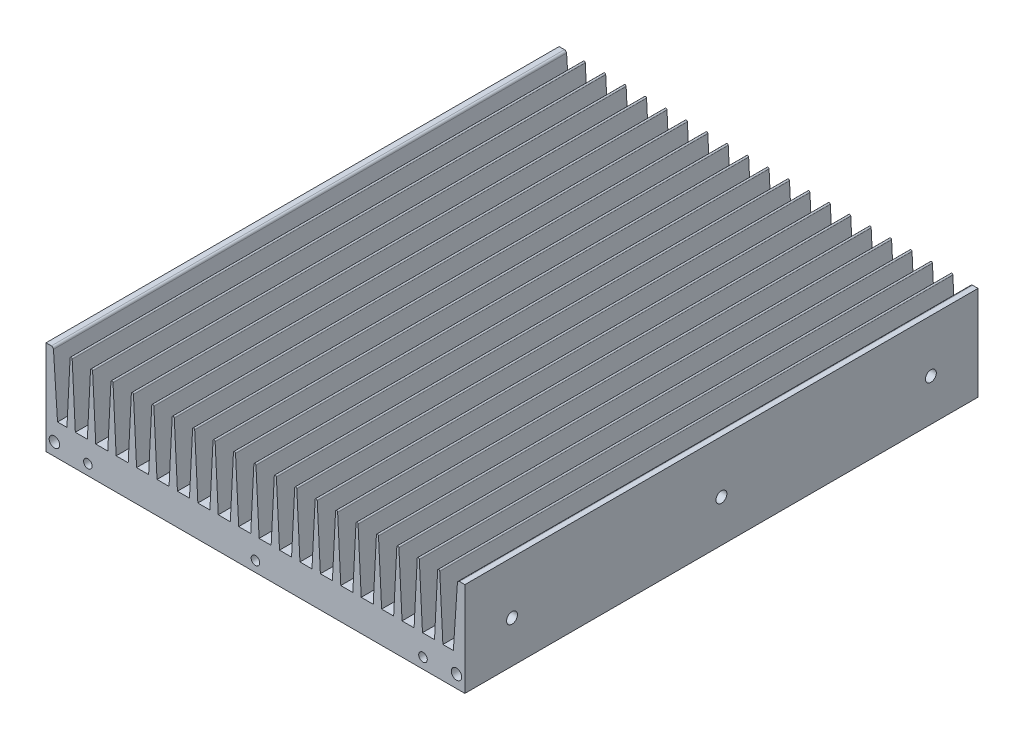
SolidWorks part; units mm, degrees
ref_plane "Спереди" through (0, 0, 0) normal (0, 0, 1) x (1, 0, 0)
ref_plane "Сверху" through (0, 0, 0) normal (0, 1, 0) x (1, 0, 0)
ref_plane "Справа" through (0, 0, 0) normal (1, 0, 0) x (0, 0, -1)
sketch "Эскиз1" plane through (0, 0, 0) normal (0, 0, 1) x (1, 0, 0)
  line L0 (0, 45) -> (2.5644, 45)
  line L1 (0, 0) -> (200, 0)
  line L2 (3.5622, 44.0665) -> (5.5, 15)
  line L3 (0, 45) -> (0, 0)
  line L4 (200, 45) -> (200, 0)
  line L5 (100, 63.7127) -> (100, -22.2582) construction
  line L8 (200, 45) -> (197.4356, 45)
  line L9 (196.4378, 44.0665) -> (194.5, 15)
  line L10 (5.5, 15) -> (194.5, 15)
  arc A0 (2.5644, 45) -> (3.5622, 44.0665) centre (2.5644, 44) cw
  arc A2 (197.4356, 45) -> (196.4378, 44.0665) centre (197.4356, 44) ccw
  point P18 (196.5, 45)
  dimension "D9" = 1
  dimension "D1" = 200
  dimension "D2" = 15
  dimension "D3" = 45
  dimension "D4" = 5.5
  dimension "D7" = 3.5
extrude "Вытянуть1" add sketch "Эскиз1" along normal blind 245
sketch "Эскиз2" plane through (0, 0, 245) normal (0, 0, 1) x (1, 0, 0)
  line L0 (194.5, 15) -> (5.5, 15) construction
  line L1 (11.5, 44.5) -> (10, 15)
  line L2 (12, 44.5) -> (12, 22.5548) construction
  line L3 (12.5, 44.5) -> (14, 15)
  line L4 (10, 15) -> (14, 15)
  line L6 (0, 45) -> (0, 0) construction
  arc A0 (11.5, 44.5) -> (12.5, 44.5) centre (12, 44.5) cw
  dimension "D1" = 30
  dimension "D3" = 0.5
  dimension "D2" = 4
  dimension "D4" = 12
  dimension "D5" = 1
extrude "Вытянуть3" add sketch "Эскиз2" against normal blind 245
pattern_curve "Кривая1" of "Вытянуть3" along edge at (100, 0, 0) parameters "D1"=19, "D3"=9.75, "D2"=1, "D4"=50
sketch "Эскиз3" plane through (0, 0, 245) normal (0, 0, 1) x (1, 0, 0)
  line L0 (-5.713, 5) -> (205.713, 5) construction
  line L1 (100, 80.0798) -> (100, -21.2847) construction
  line L2 (0, 45) -> (0, 0) construction
  line L3 (200, 0) -> (200, 45) construction
  line L4 (0, 0) -> (200, 0) construction
  circle A0 centre (20, 5) radius 2.05
  circle A1 centre (100, 5) radius 2.05
  circle A2 centre (180, 5) radius 2.05
  dimension "D2" = 4.1
  dimension "D1" = 5
  dimension "D3" = 20
extrude "Вырез-Вытянуть1" cut sketch "Эскиз3" against normal blind 10
sketch "Эскиз5" plane through (0, 0, 0) normal (0, 0, -1) x (-1, 0, 0)
  circle A0 centre (-180, 5) radius 2.05 construction
  circle A1 centre (-180, 5) radius 2.05
  circle A2 centre (-100, 5) radius 2.05 construction
  circle A3 centre (-100, 5) radius 2.05
  circle A4 centre (-20, 5) radius 2.05 construction
  circle A5 centre (-20, 5) radius 2.05
extrude "Вырез-Вытянуть2" cut sketch "Эскиз5" against normal blind 10
sketch "Эскиз6" plane through (0, 0, 0) normal (0, 0, -1) x (-1, 0, 0)
  line L0 (0, 0) -> (-200, 0) construction
  line L1 (0, 45) -> (0, 0) construction
  line L2 (-200, 0) -> (-200, 45) construction
  circle A0 centre (-4, 6) radius 2.5
  circle A1 centre (-196, 6) radius 2.5
  dimension "D1" = 5
  dimension "D2" = 6
  dimension "D3" = 4
  dimension "D4" = 6
  dimension "D6" = 5
  dimension "D5" = 4
extrude "Вырез-Вытянуть3" cut sketch "Эскиз6" against normal blind 8
sketch "Эскиз7" plane through (0, 0, 0) normal (-1, 0, 0) x (0, 0, 1)
  line L0 (-24.1676, 20) -> (275.3481, 20) construction
  line L1 (122.5, 109.9776) -> (122.5, -31.6981) construction
  line L2 (245, 45) -> (245, 0) construction
  line L3 (0, 45) -> (0, 0) construction
  line L4 (245, 0) -> (0, 0) construction
  circle A0 centre (22.5, 20) radius 2.6
  circle A1 centre (222.5, 20) radius 2.6
  circle A2 centre (122.5, 20) radius 2.6
  dimension "D2" = 5.2
  dimension "D3" = 200
  dimension "D1" = 20
extrude "Вырез-Вытянуть4" cut sketch "Эскиз7" against normal blind 6
sketch "Эскиз8" plane through (200, 0, 0) normal (1, 0, 0) x (0, 0, -1)
  line L0 (9.57, 30) -> (-255.3048, 30) construction
  line L1 (-245, 45) -> (0, 45) construction
  line L2 (-122.5, 20) -> (-122.5, -38.851) construction
  line L3 (0, 0) -> (0, 45) construction
  line L4 (-245, 0) -> (-245, 45) construction
  circle A0 centre (-80, 30) radius 4.5
  circle A1 centre (-165, 30) radius 3.4
  dimension "D2" = 9
  dimension "D3" = 6.8
  dimension "D5" = 80
  dimension "D1" = 15
  dimension "D4" = 80
extrude "Вырез-Вытянуть5" cut sketch "Эскиз8" against normal blind 6
sketch "Эскиз9" plane through (200, 0, 0) normal (1, 0, 0) x (0, 0, -1)
  circle A0 centre (-22.5, 20) radius 2.6 construction
  circle A1 centre (-22.5, 20) radius 2.6
  circle A2 centre (-122.5, 20) radius 2.6 construction
  circle A3 centre (-122.5, 20) radius 2.6
  circle A4 centre (-222.5, 20) radius 2.6 construction
  circle A5 centre (-222.5, 20) radius 2.6
extrude "Вырез-Вытянуть6" cut sketch "Эскиз9" against normal blind 6
cosmetic thread "Условное изображение резьбы9" parameters "D1"=4.34, "D2"=6
cosmetic thread "Условное изображение резьбы10" parameters "D1"=4.34, "D2"=6
cosmetic thread "Условное изображение резьбы11" parameters "D1"=4.34, "D2"=6
sketch "Эскиз10" plane through (0, 0, 0) normal (-1, 0, 0) x (0, 0, 1)
  circle A0 centre (165, 30) radius 3.4 construction
  circle A1 centre (165, 30) radius 3.4
  circle A2 centre (80, 30) radius 4.5 construction
  circle A3 centre (80, 30) radius 4.5
extrude "Вырез-Вытянуть7" cut sketch "Эскиз10" against normal blind 6
cosmetic thread "Условное изображение резьбы8" parameters "D1"=4.34, "D2"=8
sketch "Эскиз11" plane through (0, 0, 0) normal (-1, 0, 0) x (0, 0, 1)
  circle A0 centre (22.5, 20) radius 2.6 construction
  circle A1 centre (22.5, 20) radius 2.6
  circle A2 centre (122.5, 20) radius 2.6 construction
  circle A3 centre (122.5, 20) radius 2.6
  circle A4 centre (222.5, 20) radius 2.6 construction
  circle A5 centre (222.5, 20) radius 2.6
extrude "Вытянуть4" add sketch "Эскиз11" against normal up to surface (5.34 mm away)
sketch "Эскиз12" plane through (200, 0, 0) normal (1, 0, 0) x (0, 0, -1)
  circle A0 centre (-80, 30) radius 4.5 construction
  circle A1 centre (-80, 30) radius 4.5
  circle A2 centre (-165, 30) radius 3.4 construction
  circle A3 centre (-165, 30) radius 3.4
extrude "Вытянуть5" add sketch "Эскиз12" against normal up to surface (4.5 mm away)
sketch "Эскиз14" plane through (0, 0, 245) normal (0, 0, 1) x (1, 0, 0)
  circle A0 centre (4, 6) radius 2.5 construction
  circle A1 centre (4, 6) radius 2.5
  circle A2 centre (196, 6) radius 2.5 construction
  circle A3 centre (196, 6) radius 2.5
extrude "Вырез-Вытянуть9" cut sketch "Эскиз14" against normal blind 8
sketch "Эскиз18" plane through (0, 0, 0) normal (0, -1, 0) x (1, 0, 0)
  line L0 (63, 12.5) -> (173, 12.5) construction
  line L3 (200, 245) -> (200, 0) construction
  line L4 (0, 245) -> (200, 245) construction
  line L6 (173, 12.5) -> (173, 121.939) construction
  line L7 (0, 0) -> (200, 0) construction
  line L9 (63, 12.5) -> (63, 136.1196) construction
  line L11 (101.5, 132.5) -> (135, 132.5) construction
  circle A0 centre (118, 203) radius 2.1
  circle A6 centre (63, 12.5) radius 1.6
  circle A7 centre (173, 12.5) radius 1.6
  circle A8 centre (173, 162.5) radius 1.6
  circle A9 centre (63, 162.5) radius 1.6
  circle A10 centre (101.5, 132.5) radius 1.3
  circle A11 centre (135, 132.5) radius 1.3
  circle A12 centre (148, 94.5) radius 2.6
  dimension "D2" = 110
  dimension "D3" = 50
  dimension "D4" = 82
  dimension "D5" = 42
  dimension "D6" = 12.5
  dimension "D7" = 4.2
  dimension "D8" = 27
  dimension "D13" = 3.2
  dimension "D16" = 150
  dimension "D17" = 30
  dimension "D18" = 33.5
  dimension "D20" = 2.6
  dimension "D23" = 5.2
  dimension "D19" = 38
  dimension "D15" = 110
  dimension "D21" = 82
extrude "Вырез-Вытянуть11" cut sketch "Эскиз18" against normal blind 8
cosmetic thread "Условное изображение резьбы22" parameters "D2"=4
cosmetic thread "Условное изображение резьбы23" parameters "D2"=4
cosmetic thread "Условное изображение резьбы24" parameters "D2"=4
cosmetic thread "Условное изображение резьбы25" parameters "D2"=4
cosmetic thread "Условное изображение резьбы26" parameters "D2"=3
cosmetic thread "Условное изображение резьбы27" parameters "D2"=3
cosmetic thread "Условное изображение резьбы28" parameters "D2"=3
cosmetic thread "Условное изображение резьбы29" parameters "D2"=3
cosmetic thread "Условное изображение резьбы30" parameters "D2"=6
cosmetic thread "Условное изображение резьбы31" parameters "D2"=5
